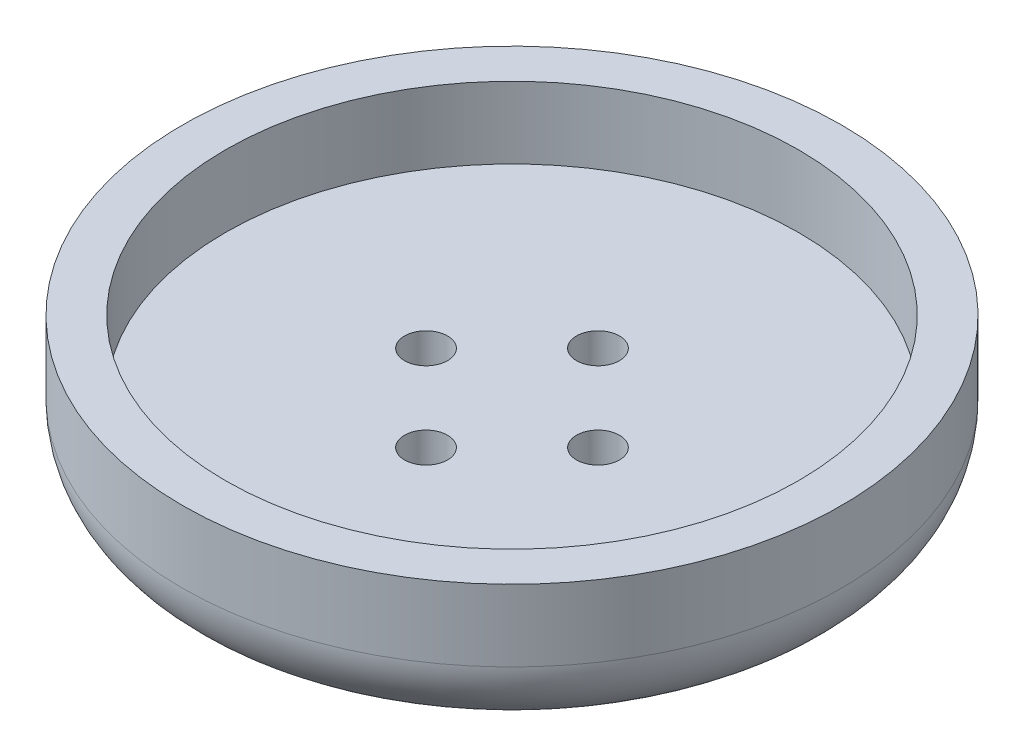
SolidWorks part; units mm, degrees
material "1060-H18"
ref_plane "Front Plane" through (0, 0, 0) normal (0, 0, 1) x (1, 0, 0)
ref_plane "Top Plane" through (0, 0, 0) normal (0, 1, 0) x (1, 0, 0)
ref_plane "Right Plane" through (0, 0, 0) normal (1, 0, 0) x (0, 0, -1)
sketch "Sketch6" plane through (0, 0, 0) normal (0, 1, 0) x (1, 0, 0)
  circle A0 centre (0, 0) radius 23
extrude "Boss-Extrude3" add sketch "Sketch6" along normal blind 25
sketch "Sketch7" plane through (0, 0, 0) normal (0, 1, 0) x (1, 0, 0)
  line L0 (0, 0) -> (-6, 0) construction
  line L1 (0, 0) -> (0, 6) construction
  circle A0 centre (-6, 0) radius 1.5
  circle A1 centre (0, 6) radius 1.5
  circle A2 centre (6, 0) radius 1.5
  circle A3 centre (0, -6) radius 1.5
  dimension "D1" = 90
extrude "Cut-Extrude2" cut sketch "Sketch7" along normal blind 5
sketch "Sketch8" plane through (0, 25, 0) normal (0, 1, 0) x (1, 0, 0)
  line L0 (0, 0) -> (-13.8564, -8) construction
  line L1 (0, 0) -> (0, 16) construction
  circle A0 centre (-13.8564, -8) radius 1.25
  circle A1 centre (0, 16) radius 1.25
  circle A2 centre (13.8564, -8) radius 1.25
  dimension "D1" = 120
extrude "Cut-Extrude3" cut sketch "Sketch8" against normal blind 5
sketch "Sketch9" plane through (0, 25, 0) normal (0, 1, 0) x (1, 0, 0)
  circle A0 centre (0, 0) radius 4
extrude "Boss-Extrude4" add sketch "Sketch9" along normal blind 2
sketch "Sketch10" plane through (0, 0, 0) normal (0, -1, 0) x (1, 0, 0)
  circle A0 centre (0, 0) radius 2
extrude "Boss-Extrude5" add sketch "Sketch10" along normal blind 3
fillet "Fillet1" radius 5 1 edges at (0, 0, 23)
fillet "Fillet2" radius 2 1 edges at (0, 25, 23)
sketch "Sketch11" plane through (0, 0, 0) normal (1, 0, 0) x (0, 0, -1)
  line L0 (55, 0) -> (-55, 0) construction
  line L1 (-28.3907, 31.5956) -> (30.3567, 31.5956)
  line L2 (-28.3907, 31.5956) -> (-28.3907, 10)
  line L3 (-28.3907, 10) -> (30.3567, 10)
  line L4 (30.3567, 31.5956) -> (30.3567, 10)
  dimension "D1" = 10
extrude "Cut-Extrude4" cut sketch "Sketch11" against normal mid plane 100
sketch "Sketch12" plane through (0, 10, 0) normal (0, 1, 0) x (1, 0, 0)
  circle A0 centre (0, 0) radius 20
extrude "Cut-Extrude5" cut sketch "Sketch12" against normal blind 5
